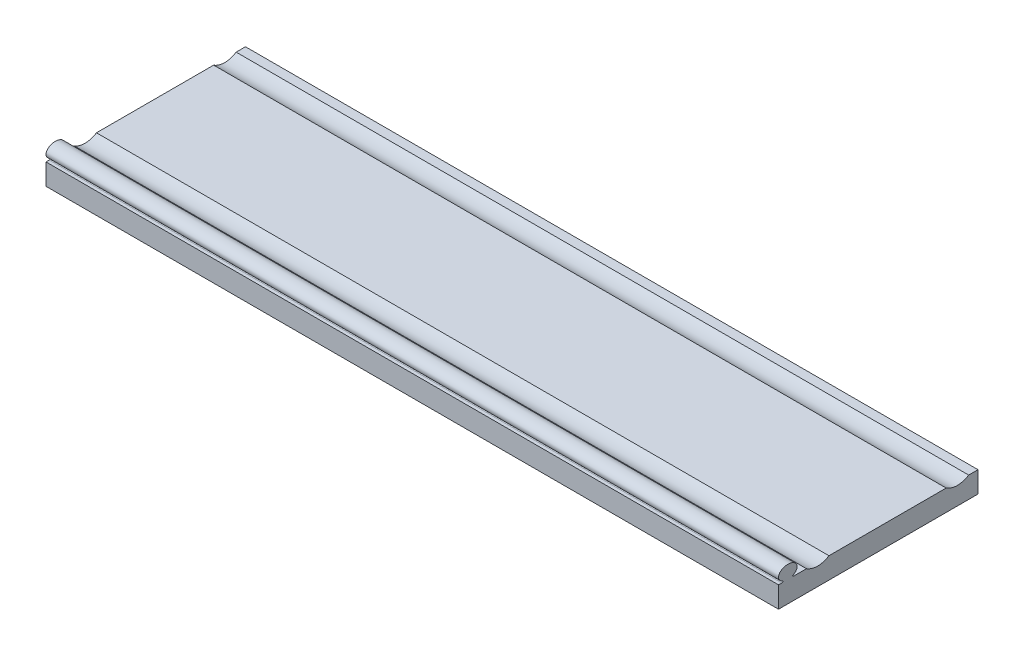
SolidWorks part; units mm, degrees
ref_plane "Front Plane" through (0, 0, 0) normal (0, 0, 1) x (1, 0, 0)
ref_plane "Top Plane" through (0, 0, 0) normal (0, 1, 0) x (1, 0, 0)
ref_plane "Right Plane" through (0, 0, 0) normal (1, 0, 0) x (0, 0, -1)
sketch "Sketch1" plane through (0, 0, 0) normal (0, 1, 0) x (1, 0, 0)
  line L1 (0, 0) -> (-7620, 0)
  line L2 (0, 0) -> (0, -1219.2)
  line L3 (0, -1219.2) -> (-7620, -1219.2)
  line L4 (-7620, 0) -> (-7620, -1219.2)
  dimension "D1" = 7620
  dimension "D2" = 1219.2
extrude "Boss-Extrude1" add sketch "Sketch1" along normal blind 220
sketch "Sketch2" plane through (0, 0, 0) normal (1, 0, 0) x (0, 0, -1)
  line L0 (-609.6, 220) -> (-609.6, 0) construction
  line L1 (-1219.2, 220) -> (0, 220) construction
  line L2 (-1219.2, 0) -> (0, 0) construction
  line L3 (-1453.2687, 220) -> (-1550.3704, 220)
  line L4 (-1550.3704, 220) -> (-1550.3704, 0)
  line L5 (-1550.3704, 0) -> (-1219.2, 0)
  line L6 (-1219.2, 0) -> (-1219.2, 220)
  line L7 (0, 0) -> (0, 220)
  line L8 (331.1704, 0) -> (0, 0)
  line L9 (331.1704, 220) -> (331.1704, 0)
  line L10 (234.0687, 220) -> (331.1704, 220)
  arc A0 (-1453.2687, 220) -> (-1219.2, 220) centre (-1336.2343, 399.3244) ccw
  arc A1 (234.0687, 220) -> (0, 220) centre (117.0343, 399.3244) cw
extrude "Boss-Extrude2" add sketch "Sketch2" against normal up to surface (7620 mm away) up to face at (-7620, 110, 609.6)
sketch "Sketch3" plane through (0, 0, 0) normal (1, 0, 0) x (0, 0, -1)
  line L0 (-1550.3704, 220) -> (-1583.9931, 220)
  line L1 (-1743.955, 220) -> (-1743.955, 0)
  line L2 (-1743.955, 0) -> (-1550.3704, 0)
  line L3 (-1550.3704, 0) -> (-1550.3704, 220)
  line L4 (-1710.3323, 220) -> (-1743.955, 220)
  arc A0 (-1710.3323, 220) -> (-1695.4838, 229.1567) centre (-1710.3323, 236.6175) ccw
  arc A1 (-1598.8415, 229.1567) -> (-1583.9931, 220) centre (-1583.9931, 236.6175) ccw
  ellipse E0 centre (-1647.1627, 288.5755) end of major axis (-1550.3704, 288.5755) minor radius 68.5755 (-1598.8415, 229.1567) -> (-1695.4838, 229.1567) ccw
extrude "Boss-Extrude3" add sketch "Sketch3" against normal up to surface (7620 mm away) up to face at (-7620, 156.2971, 609.6)
